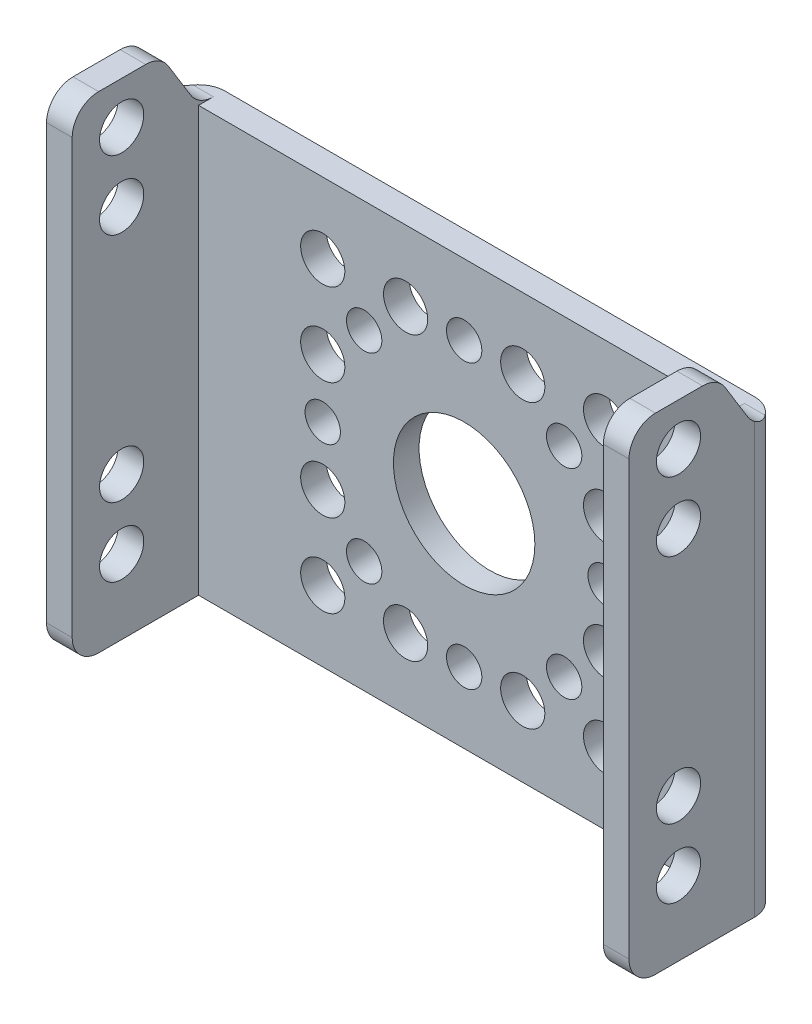
SolidWorks part; units mm, degrees
ref_plane "Front Plane" through (0, 0, 0) normal (0, 0, 1) x (1, 0, 0)
ref_plane "Top Plane" through (0, 0, 0) normal (0, 1, 0) x (1, 0, 0)
ref_plane "Right Plane" through (0, 0, 0) normal (1, 0, 0) x (0, 0, -1)
sketch "Sketch1" plane through (0, 0, 0) normal (0, 0, 1) x (1, 0, 0)
  line L1 (0, 0) -> (32.95, 0)
  line L2 (0, 0) -> (0, 24)
  line L3 (0, 24) -> (32.95, 24)
  line L4 (32.95, 0) -> (32.95, 24)
extrude "Boss-Extrude1" add sketch "Sketch1" along normal blind 1.45
sketch "Sketch3" plane through (0, 0, 1.45) normal (0, 0, 1) x (1, 0, 0)
  line L0 (32.95, 24) -> (0, 24) construction
  line L1 (0, 24) -> (0, 0) construction
  circle A0 centre (16.475, 12) radius 4
  dimension "D1" = 12
  dimension "D2" = 16.475
extrude "Cut-Extrude1" cut sketch "Sketch3" against normal through all
sketch "Sketch4" plane through (0, 0, 1.45) normal (0, 0, 1) x (1, 0, 0)
  circle A0 centre (16.475, 20) radius 1
  dimension "D1" = 8
extrude "Cut-Extrude2" cut sketch "Sketch4" against normal through all
pattern_circular "CirPattern1" count 8 over 360 about axis through (16.475, 12, 0) along (0, 0, 1) of "Cut-Extrude2"
sketch "Sketch5" plane through (0, 0, 1.45) normal (0, 0, 1) x (1, 0, 0)
  line L0 (16.475, 12) -> (22.1319, 17.6569) construction
  line L1 (22.1319, 17.6569) -> (28.475, 24) construction
  line L2 (32.95, 24) -> (0, 24) construction
  line L3 (24.475, 12) -> (24.475, 20) construction
  line L4 (16.475, 12) -> (24.475, 15.3129) construction
sketch "Sketch6" plane through (0, 0, 1.45) normal (0, 0, 1) x (1, 0, 0)
  circle A0 centre (24.475, 15.3129) radius 1.25
extrude "Cut-Extrude3" cut sketch "Sketch6" against normal blind 1.45
sketch "Sketch7" plane through (0, 0, 1.45) normal (0, 0, 1) x (1, 0, 0)
  circle A0 centre (24.475, 20) radius 1.25
extrude "Cut-Extrude4" cut sketch "Sketch7" against normal blind 1.45
pattern_circular "CirPattern2" count 4 over 360 about axis through (16.475, 12, 0) along (0, 0, 1) of "Cut-Extrude4"
pattern_circular "CirPattern3" count 8 over 360 about axis through (16.475, 12, 0) along (0, 0, 1) of "Cut-Extrude3"
sketch "Sketch8" plane through (0, 0, 1.45) normal (0, 0, 1) x (1, 0, 0)
  line L1 (0, 0) -> (1.45, 0)
  line L2 (0, 0) -> (0, 27.5)
  line L3 (0, 27.5) -> (1.45, 27.5)
  line L4 (1.45, 0) -> (1.45, 27.5)
extrude "Boss-Extrude2" add sketch "Sketch8" along normal blind 7.15
sketch "Sketch9" plane through (0, 0, 0) normal (-1, 0, 0) x (0, 0, 1)
  line L0 (1.45, 27.5) -> (1.45, 24)
  line L1 (1.45, 27.5) -> (3.6, 27.5)
  line L2 (1.45, 24) -> (3.6, 24)
  line L3 (3.6, 27.5) -> (3.6, 24)
  line L5 (8.6, 27.5) -> (8.6, 0) construction
  dimension "D1" = 5
extrude "Cut-Extrude5" cut sketch "Sketch9" against normal up to body
sketch "Sketch11" plane through (1.45, 0, 0) normal (1, 0, 0) x (0, 0, -1)
  line L0 (-3.6, 27.5) -> (-1.45, 24)
  line L1 (-1.45, 24) -> (-3.6, 24)
  line L2 (-3.6, 24) -> (-3.6, 27.5)
extrude "Boss-Extrude3" add sketch "Sketch11" against normal up to surface (1.45 mm away) up to face at (0, 17.1667, 4.3667)
fillet "Fillet1" radius 1.5 4 edges at (0.725, 0, 8.6) (0.725, 27.5, 8.6) (0.725, 27.5, 3.6) (0.725, 24, 1.45)
fillet "Fillet2" radius 1.5 1 edges at (0, 12, 0)
sketch "Sketch12" plane through (0, 0, 0) normal (-1, 0, 0) x (0, 0, 1)
  line L0 (7.1, 0) -> (1.5, 0) construction
  line L1 (8.6, 26) -> (8.6, 1.5) construction
  circle A0 centre (5.8, 4.2) radius 1.25
  dimension "D1" = 4.2
  dimension "D2" = 2.8
extrude "Cut-Extrude6" cut sketch "Sketch12" against normal blind 1.5
sketch "Sketch13" plane through (0, 0, 0) normal (-1, 0, 0) x (0, 0, 1)
  line L0 (8.6, 26) -> (8.6, 1.5) construction
  circle A0 centre (5.8, 21.2) radius 1.25
  dimension "D1" = 2.8
  dimension "D2" = 17
extrude "Cut-Extrude7" cut sketch "Sketch13" against normal blind 1.5
sketch "Sketch14" plane through (0, 0, 0) normal (-1, 0, 0) x (0, 0, 1)
  line L1 (8.6, 26) -> (8.6, 1.5) construction
  circle A0 centre (5.8, 25.1) radius 1.25
  dimension "D1" = 3.9
  dimension "D2" = 2.8
extrude "Cut-Extrude8" cut sketch "Sketch14" against normal blind 1.5
sketch "Sketch15" plane through (0, 0, 0) normal (-1, 0, 0) x (0, 0, 1)
  line L0 (8.6, 26) -> (8.6, 1.5) construction
  circle A0 centre (5.8, 8.1) radius 1.25
  dimension "D1" = 2.8
  dimension "D2" = 17
extrude "Cut-Extrude9" cut sketch "Sketch15" against normal blind 1.5
ref_plane "Plane1" through (16.475, 0, 0) normal (1, 0, 0) x (0, 0, -1)
mirror "Mirror3" about plane through (16.475, 0, 0) normal (1, 0, 0) of "Boss-Extrude2"
mirror "Mirror5" about plane through (16.475, 0, 0) normal (1, 0, 0) of "Cut-Extrude5"
sketch "Sketch17" plane through (31.5, 0, 0) normal (-1, 0, 0) x (0, 0, 1)
  line L0 (1.45, 24) -> (3.6, 27.5)
  line L1 (3.6, 27.5) -> (3.6, 24)
  line L2 (3.6, 24) -> (1.45, 24)
extrude "Boss-Extrude5" add sketch "Sketch17" against normal up to surface (1.45 mm away) up to face at (32.95, 17.1667, 4.0667)
mirror "Mirror8" about plane through (16.475, 0, 0) normal (1, 0, 0) of "Cut-Extrude8", "Cut-Extrude7", "Cut-Extrude6", "Cut-Extrude9"
fillet "Fillet3" radius 1.5 4 edges at (32.225, 27.5, 8.6) (32.225, 0, 8.6) (32.225, 27.5, 3.6) (32.225, 24, 1.45)
fillet "Fillet4" radius 1.5 1 edges at (32.95, 12, 0)
